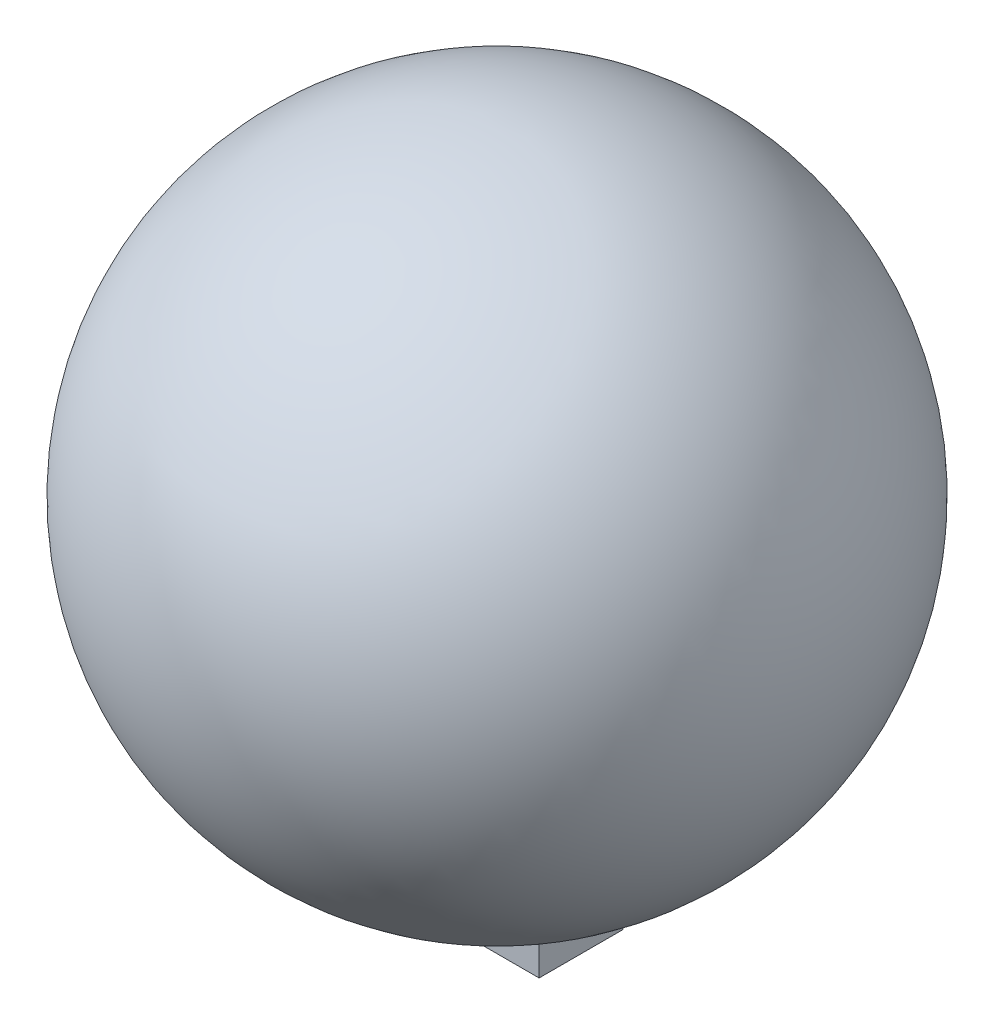
SolidWorks part; units mm, degrees
ref_plane "Plan de face" through (0, 0, 0) normal (0, 0, 1) x (1, 0, 0)
ref_plane "Plan de dessus" through (0, 0, 0) normal (0, 1, 0) x (1, 0, 0)
ref_plane "Plan de droite" through (0, 0, 0) normal (1, 0, 0) x (0, 0, -1)
sketch "Esquisse1" plane through (0, 0, 0) normal (0, 0, 1) x (1, 0, 0)
  line L0 (0, 0) -> (-20, 0)
  line L1 (0, 0) -> (0, 171.1119) construction
  line L2 (0, 3) -> (-19.1237, 3)
  line L3 (0, 70) -> (0, 67)
  line L4 (0, 3) -> (0, 0)
  arc A0 (-20, 0) -> (0, 70) centre (0, 32.1429) cw
  arc A1 (-19.1237, 3) -> (0, 67) centre (0, 32.1429) cw
  dimension "D1" = 20
  dimension "D2" = 70
  dimension "D3" = 0
  dimension "D4" = 3
revolve "Révolution3" add sketch "Esquisse1" angle 360 about L1
sketch "Esquisse2" plane through (0, 0, 0) normal (0, -1, 0) x (1, 0, 0)
  line L1 (-10, 5) -> (10, 5)
  line L2 (-10, 5) -> (-10, -5)
  line L3 (-10, -5) -> (10, -5)
  line L4 (10, 5) -> (10, -5)
  line L5 (-10, 5) -> (10, -5) construction
  line L6 (-10, -5) -> (10, 5) construction
  point P0 (0, 0)
  dimension "D1" = 10
  dimension "D2" = 20
extrude "Boss.-Extru.1" add sketch "Esquisse2" along normal blind 10
sketch "Esquisse3" plane through (0, 0, -5) normal (0, 0, -1) x (-1, 0, 0)
  line L4 (7, -3) -> (7, 0)
  line L5 (10, 0) -> (-10, 0) construction
  line L6 (-7, -3) -> (-7, 0)
  line L7 (-7, 0) -> (7, 0)
  line L8 (7, -3) -> (-7, -3)
  line L9 (-7, -3) -> (-7, -7)
  line L10 (-7, -7) -> (7, -7)
  line L11 (7, -7) -> (7, -3)
  line L13 (-7, -3) -> (-7, -7)
  line L14 (-7, -7) -> (7, -7)
  line L15 (7, -7) -> (7, -3)
  dimension "D1" = 3
extrude "Enlèv. mat.-Extru.2" cut sketch "Esquisse3" against normal blind 10
